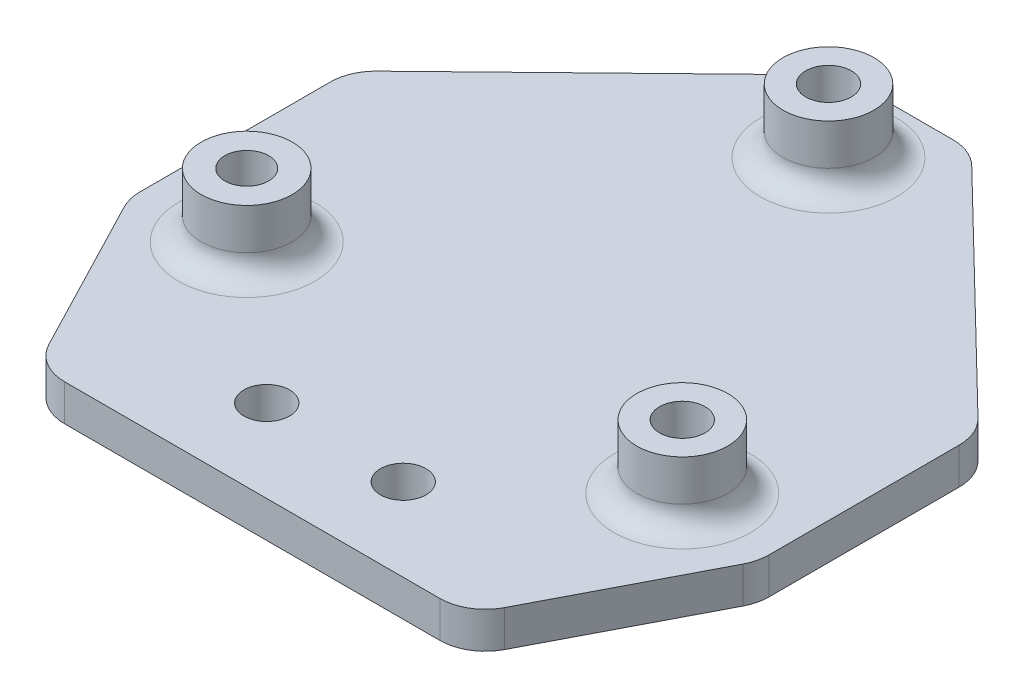
SolidWorks part; units mm, degrees
material "ABS"
ref_plane "Front Plane" through (0, 0, 0) normal (0, 0, 1) x (1, 0, 0)
ref_plane "Top Plane" through (0, 0, 0) normal (0, 1, 0) x (1, 0, 0)
ref_plane "Right Plane" through (0, 0, 0) normal (1, 0, 0) x (0, 0, -1)
sketch "Sketch1" plane through (0, 0, 0) normal (0, 1, 0) x (1, 0, 0)
  line L0 (-2.9978, 1.6275) -> (-2.9978, -22.6068)
  line L1 (-2.9978, -22.6068) -> (7.9116, -43.613)
  line L2 (7.9116, -43.613) -> (31.5573, -43.613)
  line L3 (31.5573, -47.7519) -> (31.5573, 17.1115) construction
  line L4 (24.3856, 28.2372) -> (-2.9978, 1.6275)
  line L5 (55.2031, -43.613) -> (31.5573, -43.613)
  line L6 (66.1125, -22.6068) -> (55.2031, -43.613)
  line L7 (66.1125, 1.6275) -> (66.1125, -22.6068)
  line L8 (38.729, 28.2372) -> (66.1125, 1.6275)
  line L9 (-2.9978, 7.2109) -> (66.1125, 7.2109) construction
  line L10 (66.1125, -7.7891) -> (-2.9978, -7.7891) construction
  line L11 (24.3856, 28.2372) -> (38.729, 28.2372)
  line L12 (55.4901, -20.2891) -> (7.6245, -20.2891) construction
  circle A1 centre (55.4901, -20.2891) radius 2.5
  circle A2 centre (31.5573, 19.7109) radius 2.5
  circle A3 centre (7.6245, -20.2891) radius 2.5
  circle A4 centre (31.5573, 19.7109) radius 12.5 construction
  circle A5 centre (7.6245, -20.2891) radius 12.5 construction
  point P6 (31.5573, 35.2062)
  point P22 (31.5573, -20.2891)
  dimension "D1" = 5
  dimension "D2" = 5
  dimension "D3" = 25
  dimension "D4" = 25
  dimension "D5" = 15
extrude "Boss-Extrude2" add sketch "Sketch1" along normal blind 4
fillet "Fillet1" radius 5 8 edges at (7.9116, 2, 43.613) (55.2031, 2, 43.613) (66.1125, 2, 22.6068) (66.1125, 2, -1.6275) (-2.9978, 2, -1.6275) (-2.9978, 2, 22.6068) (24.3856, 2, -28.2372) (38.729, 2, -28.2372)
sketch "Sketch2" plane through (0, 4, 0) normal (0, 1, 0) x (1, 0, 0)
  circle A0 centre (31.5573, 19.7109) radius 5
  circle A1 centre (31.5573, 19.7109) radius 2.5
  circle A2 centre (55.4901, -20.2891) radius 2.5
  circle A3 centre (55.4901, -20.2891) radius 5
  circle A4 centre (7.6245, -20.2891) radius 2.4106
  circle A5 centre (7.6245, -20.2891) radius 5
  dimension "D1" = 10
  dimension "7.5" = 10
  dimension "D2" = 10
extrude "Boss-Extrude3" add sketch "Sketch2" along normal blind 7
fillet "Fillet2" radius 2.5 3 edges at (55.4901, 4, 25.2891) (7.6245, 4, 25.2891) (31.5573, 4, -14.7109)
sketch "Sketch3" plane through (0, 4, 0) normal (0, 1, 0) x (1, 0, 0)
  line L0 (31.5573, 28.2372) -> (31.5573, -43.613) construction
  line L1 (36.6998, 28.2372) -> (26.4149, 28.2372) construction
  line L2 (10.9489, -43.613) -> (52.1657, -43.613) construction
  line L3 (39.0573, -34.522) -> (24.0573, -34.522) construction
  circle A0 centre (39.0573, -34.522) radius 2.5
  circle A1 centre (24.0573, -34.522) radius 2.5
  dimension "D1" = 5
  dimension "D2" = 5
  dimension "D3" = 7.5
  dimension "D4" = 7.5
extrude "Cut-Extrude1" cut sketch "Sketch3" against normal through all
